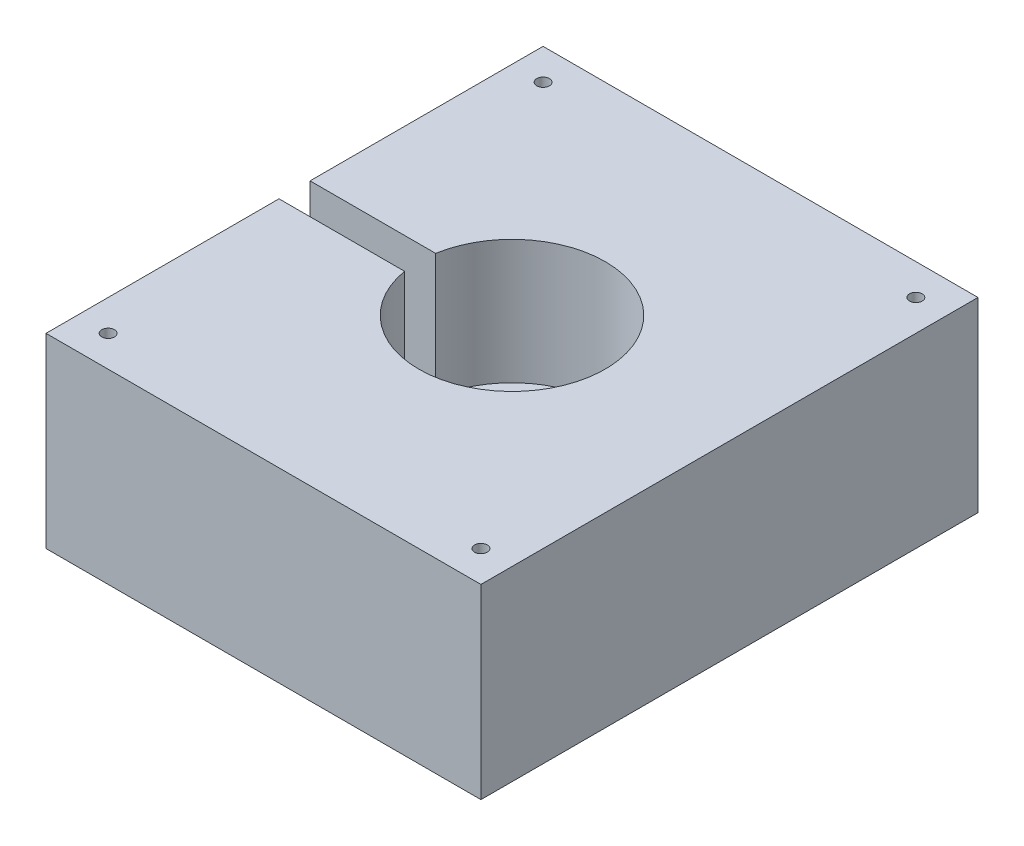
SolidWorks part; units mm, degrees
ref_plane "Front Plane" through (0, 0, 0) normal (0, 0, 1) x (1, 0, 0)
ref_plane "Top Plane" through (0, 0, 0) normal (0, 1, 0) x (1, 0, 0)
ref_plane "Right Plane" through (0, 0, 0) normal (1, 0, 0) x (0, 0, -1)
sketch "Sketch1" plane through (0, 0, 0) normal (0, 1, 0) x (1, 0, 0)
  line L1 (-88.9, -101.6) -> (88.9, -101.6)
  line L2 (-88.9, -101.6) -> (-88.9, 101.6)
  line L3 (-88.9, 101.6) -> (88.9, 101.6)
  line L4 (88.9, -101.6) -> (88.9, 101.6)
  line L5 (-88.9, -101.6) -> (88.9, 101.6) construction
  line L6 (-88.9, 101.6) -> (88.9, -101.6) construction
  point P0 (0, 0)
  point P6 (0, 0)
  dimension "D1" = 203.2
  dimension "D2" = 177.8
extrude "Boss-Extrude1" add sketch "Sketch1" along normal blind 76.2
hole_wizard "#6 (0.204) Diameter Hole1" positions "Sketch2" profile "Sketch3" hole size "#6" standard "ANSI Inch"
sketch "Sketch2" plane through (0, 76.2, 0) normal (0, 1, 0) x (1, 0, 0)
  line L3 (-76.2, 88.9) -> (76.2, 88.9) construction
  line L4 (-76.2, 88.9) -> (-76.2, -88.9) construction
  line L5 (-76.2, -88.9) -> (76.2, -88.9) construction
  line L6 (76.2, 88.9) -> (76.2, -88.9) construction
  line L7 (88.9, 101.6) -> (-88.9, 101.6) construction
  line L8 (-88.9, 101.6) -> (-88.9, -101.6) construction
  line L9 (0, 88.9) -> (0, -88.9) construction
  point P2 (76.2, 88.9)
  point P4 (76.2, -88.9)
  point P6 (-76.2, -88.9)
  point P14 (-76.2, 88.9)
  point P153 (0, 0)
  point P155 (0, 0)
  dimension "D3" = 12.7
  dimension "D4" = 12.7
sketch "Sketch3" plane through (76.2, 76.2, -88.9) normal (1, 0, 0) x (0, 0, 1)
  line L0 (0, 0) -> (0, 13.4947)
  line L1 (0, 13.4947) -> (2.5908, 11.938)
  line L2 (2.5908, 11.938) -> (2.5908, 0)
  line L5 (2.5908, 0) -> (0, 0)
  line L10 (0, 13.4947) -> (-2.5908, 11.938) construction
  line L11 (0, -6.35) -> (0, 107.95) construction
  dimension "Hole Dia." = 5.1816
  dimension "Hole Depth" = 11.938
  dimension "Drill Angle" = 118
ref_plane "Plane1" through (0, 25.4, 0) normal (0, -1, 0) x (-1, 0, 0)
sketch "Sketch4" plane through (0, 76.2, 0) normal (0, 1, 0) x (1, 0, 0)
  line L0 (-88.9, 101.6) -> (-88.9, -101.6) construction
  line L1 (12.7, 6.35) -> (-88.9, 6.35)
  line L2 (12.7, 6.35) -> (12.7, -6.35)
  line L3 (12.7, -6.35) -> (-88.9, -6.35)
  line L4 (-88.9, 6.35) -> (-88.9, -6.35)
  line L5 (12.7, 6.35) -> (-88.9, -6.35) construction
  line L6 (12.7, -6.35) -> (-88.9, 6.35) construction
  circle A0 centre (0, 0) radius 38.1
  point P3 (-38.1, 0)
  line M8 (-88.9, 101.6) -> (-88.9, -101.6)
  dimension "D1" = 76.2
  dimension "D2" = 12.7
extrude "Cut-Extrude1" cut sketch "Sketch4" against normal up to surface (50.8 mm away) contours L3 A0 L1 L2 | L1 A0 L3 L2 | A0 L1 L3 M8
